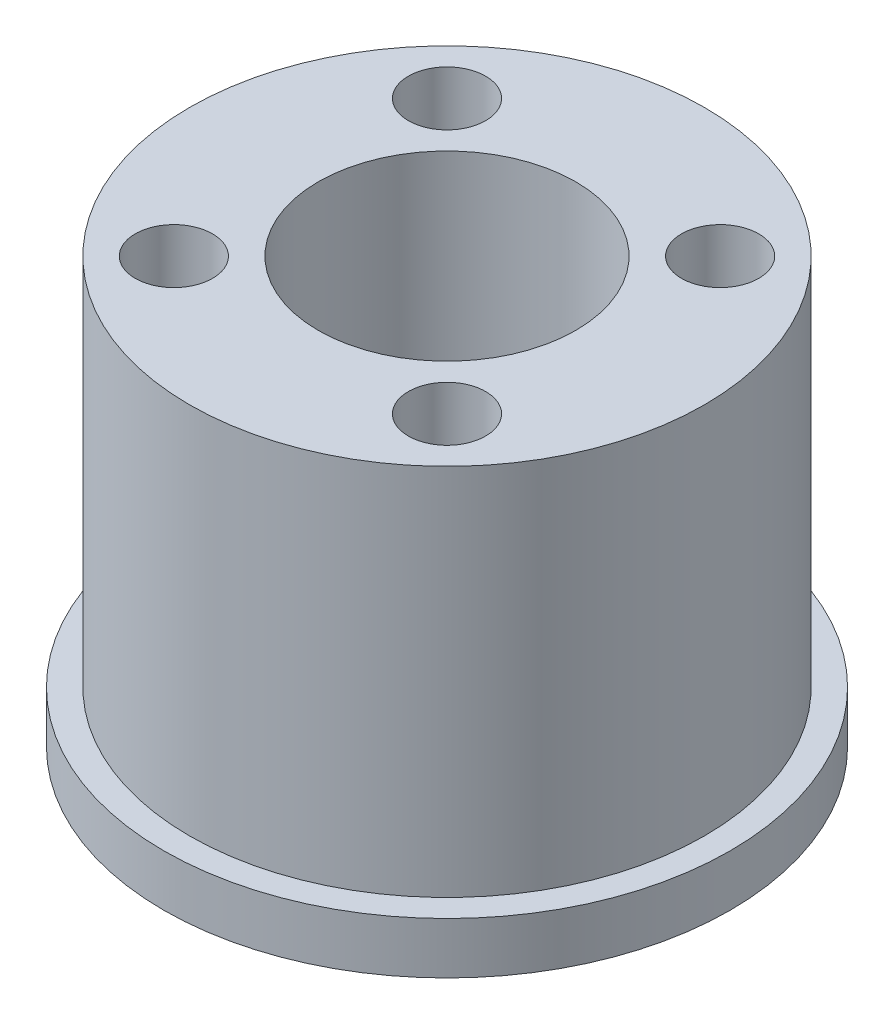
SolidWorks part; units mm, degrees
ref_plane "前视基准面" through (0, 0, 0) normal (0, 0, 1) x (1, 0, 0)
ref_plane "上视基准面" through (0, 0, 0) normal (0, 1, 0) x (1, 0, 0)
ref_plane "右视基准面" through (0, 0, 0) normal (1, 0, 0) x (0, 0, -1)
sketch "草图1" plane through (0, 0, 0) normal (0, 0, 1) x (1, 0, 0)
  line L0 (11, 2) -> (0, 2)
  line L1 (0, 2) -> (0, 0)
  line L2 (0, 0) -> (11, 0)
  line L3 (11, 0) -> (11, 2)
  line L4 (0, 2) -> (0, 0) construction
revolve "旋转1" add sketch "草图1" angle 360 about L4
sketch "草图2" plane through (0, 2, 0) normal (0, 1, 0) x (-1, 0, 0)
  circle A0 centre (0, 0) radius 10
extrude "凸台-拉伸1" add sketch "草图2" along normal blind 14.5
hole_wizard "Ø3.0 (3) 直径孔1" positions "草图4" profile "草图3" hole size "Ø3.0" standard "ANSI Metric"
sketch "草图4" plane through (0, 16.5, 0) normal (0, 1, 0) x (1, 0, 0)
  point P0 (5.3033, 5.3033)
  point P1 (5.3033, -5.3033)
  point P2 (-5.3033, -5.3033)
  point P3 (-5.3033, 5.3033)
sketch "草图3" plane through (5.3033, 16.5, -5.3033) normal (1, 0, 0) x (0, 0, 1)
  line L0 (0, 0) -> (0, 6)
  line L1 (0, 6) -> (1.5, 6)
  line L2 (1.5, 6) -> (1.5, 0)
  line L5 (1.5, 0) -> (0, 0)
  line L10 (0, 6) -> (-1.5, 6) construction
  line L11 (0, -6.35) -> (0, 107.95) construction
  dimension "孔直径" = 3
  dimension "孔深度" = 6
  dimension "导头角度" = 180
hole_wizard "Ø10.0 (10) 直径孔1" positions "草图6" profile "草图5" hole size "Ø10.0" standard "ANSI Metric"
sketch "草图6" plane through (0, 0, 0) normal (0, -1, 0) x (-1, 0, 0)
  point P0 (0, 0)
sketch "草图5" plane through (0, 0, 0) normal (1, 0, 0) x (0, 0, -1)
  line L0 (0, 0) -> (0, 16.5)
  line L1 (0, 16.5) -> (5, 16.5)
  line L2 (5, 16.5) -> (5, 0)
  line L5 (5, 0) -> (0, 0)
  line L11 (0, -6.35) -> (0, 107.95) construction
  dimension "通孔孔直径" = 10
  dimension "通孔孔深度" = 16.5
